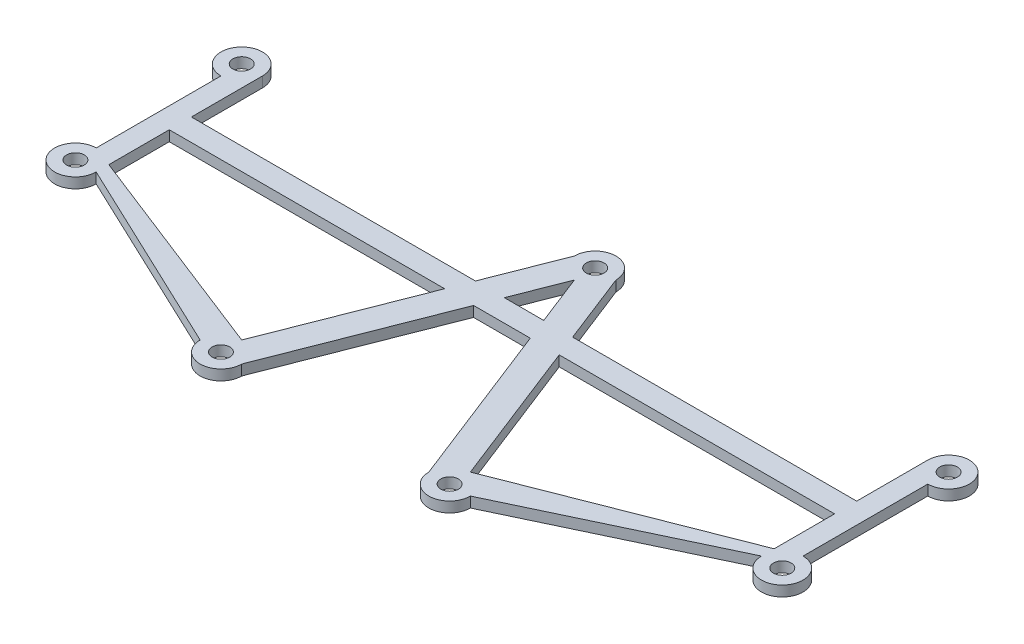
SolidWorks part; units mm, degrees
ref_plane "Front Plane" through (0, 0, 0) normal (0, 0, 1) x (1, 0, 0)
ref_plane "Top Plane" through (0, 0, 0) normal (0, 1, 0) x (1, 0, 0)
ref_plane "Right Plane" through (0, 0, 0) normal (1, 0, 0) x (0, 0, -1)
sketch "Sketch1" plane through (0, -3.5741, 0) normal (0, -1, 0) x (1, 0, 0)
  line L0 (-152.7234, 44.7005) -> (-152.7234, 20.7005)
  line L1 (-148.7234, 46.2657) -> (-148.7234, 34.6367)
  line L2 (-148.7234, 48.7005) -> (-110.7234, 66.7005)
  line L3 (-106.7234, 62.7005) -> (-148.7234, 46.2657)
  line L4 (-106.7234, 62.7005) -> (-95.7419, 34.6367)
  line L5 (-102.7234, 66.7005) -> (-90.1767, 34.6367)
  line L6 (-84.7234, 20.7005) -> (-80.934, 30.3846)
  line L7 (-62.7234, 62.7005) -> (-73.7049, 34.6367)
  line L8 (-58.7234, 66.7005) -> (-20.7234, 48.7005)
  line L9 (-62.7234, 62.7005) -> (-20.7234, 46.2657)
  line L10 (-16.7234, 44.7005) -> (-16.7234, 20.7005)
  line L11 (-20.7234, 46.2657) -> (-20.7234, 34.6367)
  line L12 (-148.7234, 30.3846) -> (-94.078, 30.3846)
  line L13 (-148.7234, 34.6367) -> (-95.7419, 34.6367)
  line L14 (-148.7234, 30.3846) -> (-148.7234, 16.7005)
  line L15 (-20.7234, 30.3846) -> (-20.7234, 16.7005)
  line L16 (-73.7049, 34.6367) -> (-20.7234, 34.6367)
  line L17 (-75.3688, 30.3846) -> (-20.7234, 30.3846)
  line L18 (-75.3688, 30.3846) -> (-80.7234, 16.7005)
  line L19 (-79.2701, 34.6367) -> (-66.7234, 66.7005)
  line L20 (-88.5128, 30.3846) -> (-84.7234, 20.7005)
  line L21 (-88.5128, 30.3846) -> (-80.934, 30.3846)
  line L22 (-90.1767, 34.6367) -> (-79.2701, 34.6367)
  line L23 (-94.078, 30.3846) -> (-88.7234, 16.7005)
  arc A0 (-148.7234, 48.7005) -> (-152.7234, 44.7005) centre (-152.7234, 48.7005) ccw
  circle A1 centre (-152.7234, 48.7005) radius 1.7
  arc A2 (-102.7234, 66.7005) -> (-110.7234, 66.7005) centre (-106.7234, 66.7005) ccw
  circle A3 centre (-106.7234, 66.7005) radius 1.7
  arc A4 (-58.7234, 66.7005) -> (-66.7234, 66.7005) centre (-62.7234, 66.7005) ccw
  circle A5 centre (-62.7234, 66.7005) radius 1.7
  circle A8 centre (-16.7234, 48.7005) radius 1.7
  arc A9 (-152.7234, 20.7005) -> (-148.7234, 16.7005) centre (-152.7234, 16.7005) ccw
  circle A10 centre (-152.7234, 16.7005) radius 1.7
  arc A11 (-88.7234, 16.7005) -> (-80.7234, 16.7005) centre (-84.7234, 16.7005) ccw
  circle A12 centre (-84.7234, 16.7005) radius 1.7
  arc A13 (-20.7234, 16.7005) -> (-16.7234, 20.7005) centre (-16.7234, 16.7005) ccw
  circle A14 centre (-16.7234, 16.7005) radius 1.7
  arc A15 (-16.7234, 44.7005) -> (-20.7234, 48.7005) centre (-16.7234, 48.7005) ccw
  point P52 (0, 0)
  dimension "D1" = 8
  dimension "D2" = 3.4
  dimension "D3" = 8
  dimension "D4" = 3.4
  dimension "D5" = 8
  dimension "D6" = 3.4
  dimension "D8" = 3.4
  dimension "D9" = 8
  dimension "D10" = 3.4
  dimension "D11" = 3.4
  dimension "D12" = 8
  dimension "D13" = 8
  dimension "D14" = 3.4
extrude "Boss-Extrude2" add sketch "Sketch1" along normal blind 2
